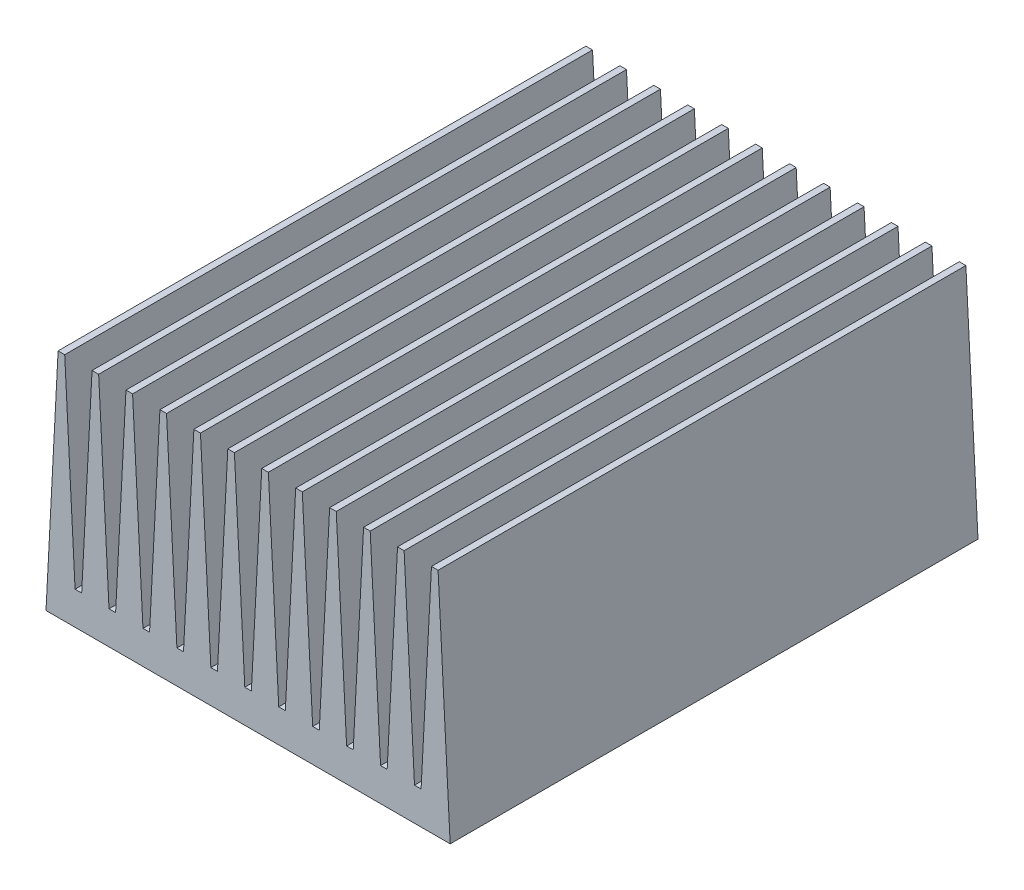
SolidWorks part; units mm, degrees
ref_plane "Front Plane" through (0, 0, 0) normal (0, 0, 1) x (1, 0, 0)
ref_plane "Top Plane" through (0, 0, 0) normal (0, 1, 0) x (1, 0, 0)
ref_plane "Right Plane" through (0, 0, 0) normal (1, 0, 0) x (0, 0, -1)
sketch "Sketch1" plane through (0, 0, 0) normal (0, 0, 1) x (1, 0, 0)
  line L0 (0, 18.9898) -> (0, 0) construction
  line L1 (0, 5) -> (0.5, 5)
  line L2 (0.5, 5) -> (2.0722, 35)
  line L3 (2.0722, 35) -> (3.0722, 35)
  line L4 (3.0722, 35) -> (4.6445, 5)
  line L5 (4.6445, 5) -> (5.1445, 5)
  line L6 (2.5722, 39.2671) -> (2.5722, 31.4538) construction
  line L7 (5.1445, 5) -> (5.6445, 5)
  line L8 (5.6445, 5) -> (7.2167, 35)
  line L9 (7.2167, 35) -> (8.2167, 35)
  line L10 (8.2167, 35) -> (9.7889, 5)
  line L11 (9.7889, 5) -> (10.2889, 5)
  line L12 (7.7167, 39.2671) -> (7.7167, 31.4538) construction
  line L13 (10.2889, 5) -> (10.7889, 5)
  line L14 (10.7889, 5) -> (12.3612, 35)
  line L15 (12.3612, 35) -> (13.3612, 35)
  line L16 (13.3612, 35) -> (14.9334, 5)
  line L17 (14.9334, 5) -> (15.4334, 5)
  line L18 (12.8612, 39.2671) -> (12.8612, 31.4538) construction
  line L19 (15.4334, 5) -> (15.9334, 5)
  line L20 (15.9334, 5) -> (17.5056, 35)
  line L21 (17.5056, 35) -> (18.5056, 35)
  line L22 (18.5056, 35) -> (20.0779, 5)
  line L23 (20.0779, 5) -> (20.5779, 5)
  line L24 (18.0056, 39.2671) -> (18.0056, 31.4538) construction
  line L25 (20.5779, 5) -> (21.0779, 5)
  line L26 (21.0779, 5) -> (22.6501, 35)
  line L27 (22.6501, 35) -> (23.6501, 35)
  line L28 (23.6501, 35) -> (25.2223, 5)
  line L29 (25.2223, 5) -> (25.7223, 5)
  line L30 (23.1501, 39.2671) -> (23.1501, 31.4538) construction
  line L31 (25.7223, 5) -> (26.2223, 5)
  line L32 (26.2223, 5) -> (27.7946, 35)
  line L33 (27.7946, 35) -> (28.7946, 35)
  line L34 (28.7946, 35) -> (30.6288, 0)
  line L36 (28.2946, 39.2671) -> (28.2946, 31.4538) construction
  line L37 (0, 5) -> (5.1445, 5) construction
  line L38 (30.3668, 5) -> (30.8668, 5) [skipped]
  line L39 (30.6288, 0) -> (0, 0)
  line L40 (0, 5) -> (0, 0)
  line L41 (28.7946, 35) -> (30.3668, 5) [skipped]
  point P10 (0, 0)
  dimension "D1" = 5
  dimension "D2" = 35
  dimension "D3" = 1
  dimension "D4" = 0.5
  dimension "D5" = 0.5
  dimension "D6" = 87
  dimension "D7" = 6
  dimension "D8" = 0.5
  dimension "D9" = 0.5
extrude "Boss-Extrude1" add sketch "Sketch1" against normal blind 80
mirror "Mirror1" about plane through (0, 0, 0) normal (1, 0, 0) of "Boss-Extrude1"
